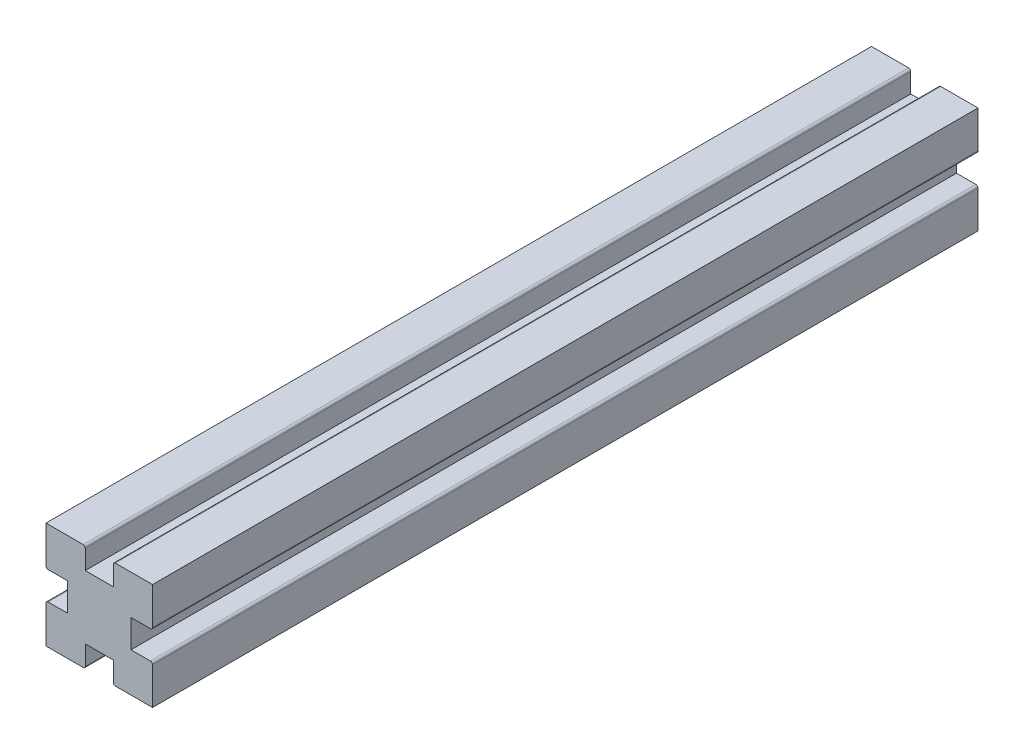
SolidWorks part; units mm, degrees
ref_plane "Front Plane" through (0, 0, 0) normal (0, 0, 1) x (1, 0, 0)
ref_plane "Top Plane" through (0, 0, 0) normal (0, 1, 0) x (1, 0, 0)
ref_plane "Right Plane" through (0, 0, 0) normal (1, 0, 0) x (0, 0, -1)
sketch "Sketch1" plane through (0, 0, 0) normal (0, 0, 1) x (1, 0, 0)
  line L0 (12.7, 3.34) -> (7.5682, 3.34)
  line L1 (-12.7, 12.7) -> (12.7, 12.7)
  line L2 (-12.7, 12.7) -> (-12.7, -12.7)
  line L3 (-12.7, -12.7) -> (12.7, -12.7)
  line L4 (12.7, 12.7) -> (12.7, -12.7)
  line L5 (-3.34, 12.7) -> (3.34, 12.7)
  line L6 (-3.34, 12.7) -> (-3.34, 7.5682)
  line L7 (-3.34, 7.5682) -> (3.34, 7.5682)
  line L8 (3.34, 12.7) -> (3.34, 7.5682)
  line L9 (12.7, 3.34) -> (12.7, -3.34)
  line L10 (12.7, -3.34) -> (7.5682, -3.34)
  line L11 (7.5682, 3.34) -> (7.5682, -3.34)
  line L12 (3.34, -12.7) -> (3.34, -7.5682)
  line L13 (3.34, -12.7) -> (-3.34, -12.7)
  line L14 (-3.34, -12.7) -> (-3.34, -7.5682)
  line L15 (3.34, -7.5682) -> (-3.34, -7.5682)
  line L16 (-12.7, -3.34) -> (-7.5682, -3.34)
  line L17 (-12.7, -3.34) -> (-12.7, 3.34)
  line L18 (-12.7, 3.34) -> (-7.5682, 3.34)
  line L19 (-7.5682, -3.34) -> (-7.5682, 3.34)
  circle A0 centre (0, 0) radius 12.7 construction
  point P4 (0, 12.7)
  point P6 (-12.7, 0)
  point P11 (0, 7.5682)
  point P29 (0, 0)
  dimension "D1" = 25.4
  dimension "D2" = 5.1318
  dimension "D3" = 6.68
  dimension "D4" = 4
extrude "Boss-Extrude1" add sketch "Sketch1" along normal blind 196.85 contours L19 L16 L2 L3 L14 L15 L12 L4 L10 L11 L0 L1 L8 L7 L6 L18
fillet "Fillet1" radius 0.5 8 edges at (-3.34, -12.7, 98.425) (3.34, -12.7, 98.425) (-12.7, -3.34, 98.425) (-12.7, 3.34, 98.425) (12.7, 3.34, 98.425) (12.7, -3.34, 98.425) (-3.34, 12.7, 98.425) (3.34, 12.7, 98.425)
